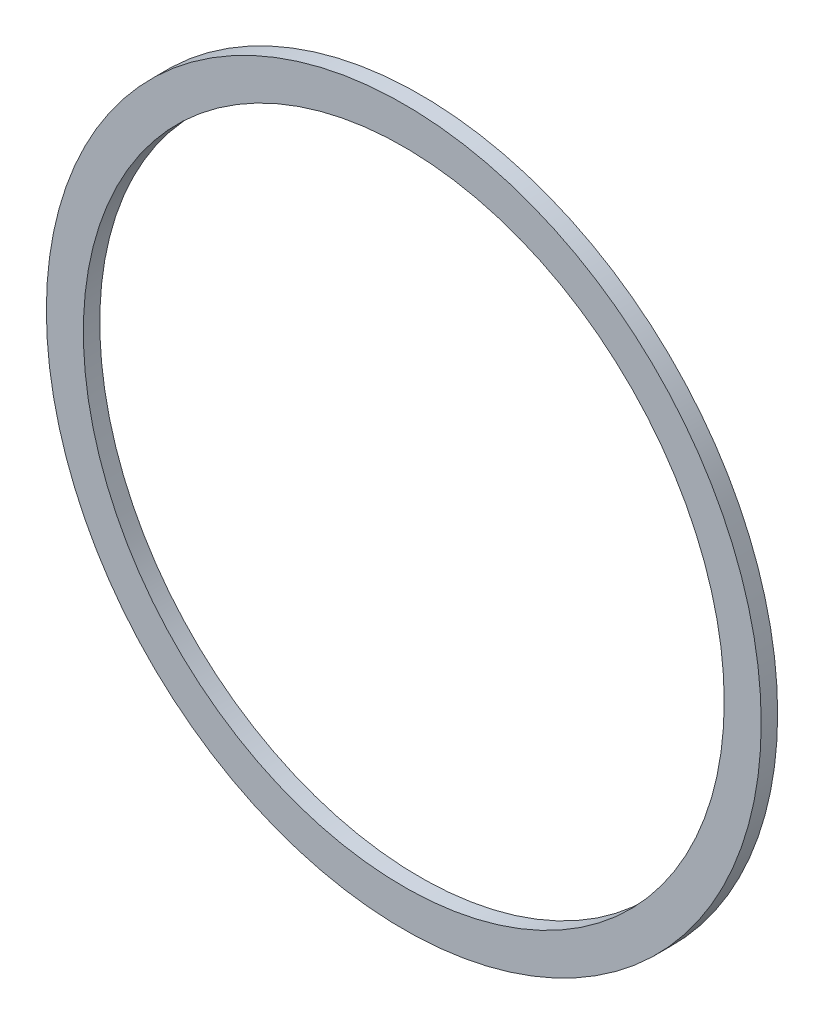
SolidWorks part; units mm, degrees
ref_plane "Plan de face" through (0, 0, 0) normal (0, 0, 1) x (1, 0, 0)
ref_plane "Plan de dessus" through (0, 0, 0) normal (0, 1, 0) x (1, 0, 0)
ref_plane "Plan de droite" through (0, 0, 0) normal (1, 0, 0) x (0, 0, -1)
sketch "Esquisse1" plane through (0, 0, 0) normal (0, 0, 1) x (1, 0, 0)
  circle A0 centre (0, 0) radius 39
  circle A1 centre (0, 0) radius 43.5
  dimension "D1" = 78
  dimension "D3" = 4.5
  dimension "D2" = 0
extrude "Boss.-Extru.1" add sketch "Esquisse1" along normal blind 2
